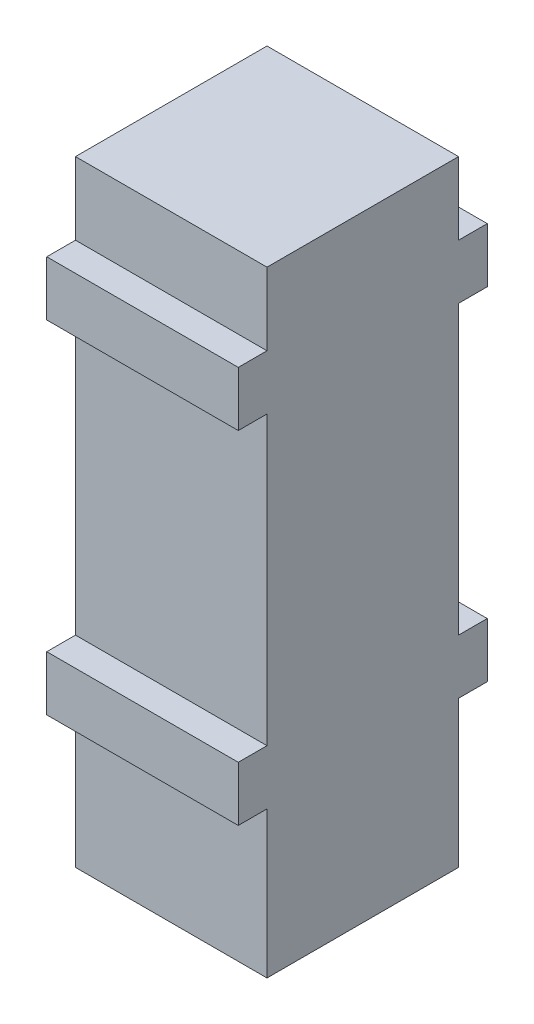
SolidWorks part; units mm, degrees
ref_plane "Front Plane" through (0, 0, 0) normal (0, 0, 1) x (1, 0, 0)
ref_plane "Top Plane" through (0, 0, 0) normal (0, 1, 0) x (1, 0, 0)
ref_plane "Right Plane" through (0, 0, 0) normal (1, 0, 0) x (0, 0, -1)
sketch "Sketch1" plane through (0, 0, 0) normal (0, 1, 0) x (1, 0, 0)
  line L0 (7, 14) -> (7, 0) construction
  line L1 (0, 0) -> (14, 0)
  line L2 (0, 0) -> (0, 14)
  line L3 (0, 14) -> (14, 14)
  line L4 (14, 0) -> (14, 14)
  line L5 (0, 7) -> (14, 7) construction
  dimension "D1" = 14
  dimension "D2" = 14
extrude "Boss-Extrude1" add sketch "Sketch1" along normal blind 45
sketch "Sketch2" plane through (0, 0, -14) normal (0, 0, -1) x (-1, 0, 0)
  line L0 (47.1168, 35.2063) -> (-202.8832, 35.2063) construction
  line L1 (-202.8832, 40.2063) -> (47.1168, 40.2063) construction
  line L2 (47.1168, 35.2063) -> (-202.8832, 35.2063) construction
  line L3 (-202.8832, 40.2063) -> (47.1168, 40.2063) construction
  line L4 (0, 45) -> (0, 0) construction
  line L5 (-14, 35.7063) -> (0, 35.7063)
  line L6 (-14, 35.7063) -> (-14, 39.7063)
  line L7 (-14, 39.7063) -> (0, 39.7063)
  line L8 (0, 35.7063) -> (0, 39.7063)
  line L9 (-14, 45) -> (-14, 0) construction
  line L10 (-7, 45) -> (-7, 0) construction
  line L11 (-14, 45) -> (0, 45) construction
  line L12 (-14, 0) -> (0, 0) construction
  line L13 (-14, 22.5) -> (0, 22.5) construction
  line L14 (47.1168, 10.2063) -> (-202.8832, 10.2063) construction
  line L15 (-202.8832, 15.2063) -> (47.1168, 15.2063) construction
  line L16 (47.1168, 10.2063) -> (-202.8832, 10.2063) construction
  line L17 (-202.8832, 15.2063) -> (47.1168, 15.2063) construction
  line L19 (-14, 14.7063) -> (0, 14.7063)
  line L20 (-14, 14.7063) -> (-14, 10.7063)
  line L21 (-14, 10.7063) -> (0, 10.7063)
  line L22 (0, 14.7063) -> (0, 10.7063)
  dimension "D1" = 0.5
  dimension "D2" = 0.5
  dimension "D3" = 0.5
  dimension "D4" = 0.5
extrude "Boss-Extrude2" add sketch "Sketch2" along normal blind 2.1
sketch "Sketch3" plane through (0, 0, 0) normal (-1, 0, 0) x (0, 0, 1)
  line L0 (-7, 45) -> (-7, 0) construction
  line L1 (-14, 45) -> (0, 45) construction
  line L2 (-14, 0) -> (0, 0) construction
ref_plane "Plane1" through (0, 0, -7) normal (0, 0, 1) x (1, 0, 0)
mirror "Mirror1" about plane through (0, 0, -7) normal (0, 0, 1) of "Boss-Extrude2"
